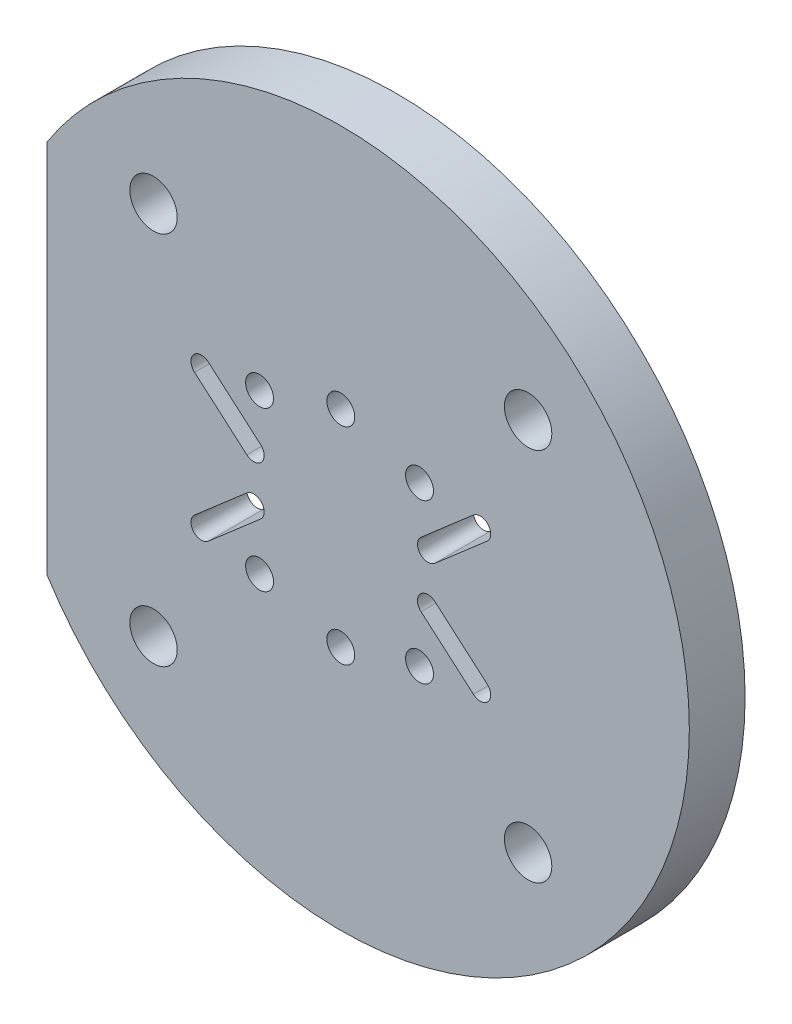
SolidWorks part; units mm, degrees
ref_plane "Plan de face" through (0, 0, 0) normal (0, 0, 1) x (1, 0, 0)
ref_plane "Plan de dessus" through (0, 0, 0) normal (0, 1, 0) x (1, 0, 0)
ref_plane "Plan de droite" through (0, 0, 0) normal (1, 0, 0) x (0, 0, -1)
sketch "Esquisse1" plane through (0, 0, 0) normal (0, 0, 1) x (1, 0, 0)
  circle A0 centre (0, 0) radius 25
  circle A1 centre (-13.435, 13.435) radius 1.7
  circle A2 centre (13.435, 13.435) radius 1.7
  circle A3 centre (13.435, -13.435) radius 1.7
  circle A4 centre (-13.435, -13.435) radius 1.7
  point P19 (0, 0)
  dimension "D1" = 50
  dimension "D5" = 19
  dimension "D6" = 3.4
  dimension "D4" = 4
extrude "Boss.-Extru.1" add sketch "Esquisse1" along normal blind 4
ref_plane "Plan1" through (0, 0, 0) normal (1, 0, 0) x (0, 0, -1)
sketch "Esquisse6" plane through (0, 0, 0) normal (0, 0, -1) x (-1, 0, 0)
  circle A0 centre (0, 0) radius 11
  dimension "D1" = 22
sketch "Esquisse8" plane through (0, 0, 4) normal (0, 0, 1) x (1, 0, 0)
  line L0 (-6.5, 2) -> (6.5, 2) construction
  line L1 (6.5, 2) -> (6.5, -2) construction
  line L2 (6.5, -2) -> (-6.5, -2) construction
  line L3 (-6.5, 2) -> (-6.5, -2) construction
  line L4 (-6.25, 1.75) -> (-6.25, 2) construction
  line L5 (-6.25, 1.75) -> (-6.5, 1.75) construction
  line L6 (-6.25, -1.75) -> (-6.5, -1.75) construction
  line L7 (-6.25, -1.75) -> (-6.25, -2) construction
  line L8 (6.25, 1.75) -> (6.25, 2) construction
  line L9 (6.25, 1.75) -> (6.5, 1.75) construction
  line L10 (6.25, -1.75) -> (6.5, -1.75) construction
  line L11 (6.25, -1.75) -> (6.25, -2) construction
  line L12 (6.5, 0) -> (-6.5, 0) construction
  circle A0 centre (-6.25, 1.75) radius 0.25
  circle A1 centre (-6.25, -1.75) radius 0.25
  circle A2 centre (6.25, 1.75) radius 0.25
  circle A3 centre (6.25, -1.75) radius 0.25
sketch "Esquisse10" plane through (0, 0, 4) normal (0, 0, 1) x (1, 0, 0)
  line L0 (-10, 0) -> (10, 0) construction
  line L1 (10, 0) -> (10, 5) construction
  line L2 (10, 5) -> (-10, 5) construction
  line L3 (-10, 5) -> (-10, 0) construction
  line L4 (6.5, -2) -> (-6.5, -2) construction
  line L5 (-6.5, 2) -> (6.5, 2) construction
  line L6 (6.5, 2) -> (6.5, -2) construction
  line L7 (6.5, 0) -> (-6.5, 0) construction
  line L8 (9.2495, -0.5365) -> (9.2495, 3.4635) construction
  line L9 (10, 0) -> (10, -5) construction
  line L10 (10, -5) -> (-10, -5) construction
  line L11 (-10, -5) -> (-10, 0) construction
  line L12 (-6.25, -1.75) -> (-10, -5) construction
  line L13 (-5.7588, -2.3168) -> (-9.5088, -5.5668)
  line L14 (-6.7412, -1.1832) -> (-10.4912, -4.4332)
  line L15 (-6.25, 1.75) -> (-10, 5) construction
  line L16 (-6.7412, 1.1832) -> (-10.4912, 4.4332)
  line L17 (-5.7588, 2.3168) -> (-9.5088, 5.5668)
  line L18 (10, -5) -> (6.25, -1.75) construction
  line L19 (9.5088, -5.5668) -> (5.7588, -2.3168)
  line L20 (10.4912, -4.4332) -> (6.7412, -1.1832)
  line L21 (10, 5) -> (6.25, 1.75) construction
  line L22 (10.4912, 4.4332) -> (6.7412, 1.1832)
  line L23 (9.5088, 5.5668) -> (5.7588, 2.3168)
  arc A0 (-5.7588, -2.3168) -> (-6.7412, -1.1832) centre (-6.25, -1.75) ccw
  arc A1 (-10.4912, -4.4332) -> (-9.5088, -5.5668) centre (-10, -5) ccw
  arc A2 (-6.7412, 1.1832) -> (-5.7588, 2.3168) centre (-6.25, 1.75) ccw
  arc A3 (-9.5088, 5.5668) -> (-10.4912, 4.4332) centre (-10, 5) ccw
  arc A4 (9.5088, -5.5668) -> (10.4912, -4.4332) centre (10, -5) ccw
  arc A5 (6.7412, -1.1832) -> (5.7588, -2.3168) centre (6.25, -1.75) ccw
  arc A6 (10.4912, 4.4332) -> (9.5088, 5.5668) centre (10, 5) ccw
  arc A7 (5.7588, 2.3168) -> (6.7412, 1.1832) centre (6.25, 1.75) ccw
  point P12 (0, 0)
  point P18 (-8.125, -3.375)
  point P24 (-8.125, 3.375)
  point P31 (8.125, -3.375)
  point P38 (8.125, 3.375)
sketch "Esquisse11" plane through (0, 0, 0) normal (0, 0, -1) x (-1, 0, 0)
  line L1 (5.8275, 5.6343) -> (-5.6451, 5.6343) construction
  line L2 (5.8275, 5.6343) -> (5.8275, -5.7587) construction
  line L3 (5.8275, -5.7587) -> (-5.6451, -5.7587) construction
  line L4 (-5.6451, 5.6343) -> (-5.6451, -5.7587) construction
  circle A0 centre (0, 7.3989) radius 1
  circle A1 centre (5.8275, 5.6343) radius 1
  circle A2 centre (5.8275, -5.7587) radius 1
  circle A3 centre (0, -7.3989) radius 1
  circle A4 centre (-5.6451, -5.7587) radius 1
  circle A5 centre (-5.6451, 5.6343) radius 1
  ellipse E0 centre (0, 0) end of major axis (8.9909, 0) minor radius 7.3989 construction
extrude "Enlèv. mat.-Extru.1" cut sketch "Esquisse11" against normal through all
sketch "Esquisse13" plane through (0, 0, 0) normal (0, 0, -1) x (-1, 0, 0)
  line L1 (21.0832, 13.435) -> (25.9868, 13.435)
  line L2 (21.0832, 13.435) -> (21.0832, -15.4591)
  line L3 (21.0832, -15.4591) -> (25.9868, -15.4591)
  line L4 (25.9868, 13.435) -> (25.9868, -15.4591)
  circle A0 centre (0, 0) radius 25 construction
extrude "Enlèv. mat.-Extru.2" cut sketch "Esquisse13" against normal through all
sketch "Esquisse14" plane through (0, 0, 0) normal (0, 0, -1) x (-1, 0, 0)
extrude "Enlèv. mat.-Extru.3" cut sketch "Esquisse10" against normal through all
equation "\"9.5.00mm\"=6"
